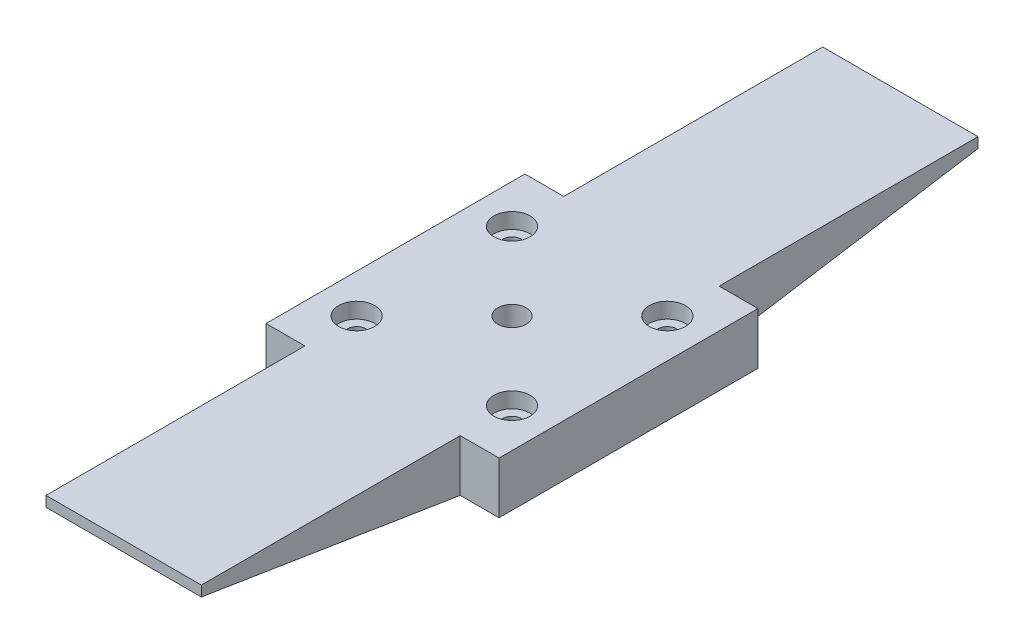
SolidWorks part; units mm, degrees
ref_plane "Front Plane" through (0, 0, 0) normal (0, 0, 1) x (1, 0, 0)
ref_plane "Top Plane" through (0, 0, 0) normal (0, 1, 0) x (1, 0, 0)
ref_plane "Right Plane" through (0, 0, 0) normal (1, 0, 0) x (0, 0, -1)
sketch "Sketch2" plane through (0, 0, 0) normal (1, 0, 0) x (0, 0, -1)
  line L0 (-75, 0) -> (75, 0)
  line L1 (75, 0) -> (75, -2)
  line L2 (75, -2) -> (25, -10)
  line L3 (25, -10) -> (-25, -10)
  line L5 (0, -33.3296) -> (0, 16.4312) construction
  line L6 (-75, -2) -> (-25, -10)
  line L7 (-75, 0) -> (-75, -2)
  point P9 (0, -10)
  point P11 (0, 0)
  dimension "D1" = 2
  dimension "D2" = 75
  dimension "D3" = 25
  dimension "D4" = 10
extrude "Boss-Extrude1" add sketch "Sketch2" along normal blind 45
sketch "Sketch3" plane through (0, -10, 0) normal (0, -1, 0) x (1, 0, 0)
  line L0 (22.5, -25) -> (22.5, 25) construction
  line L1 (45, -25) -> (0, -25) construction
  line L2 (45, 25) -> (0, 25) construction
  line L3 (0, 0) -> (45, 0) construction
  line L4 (45, 25) -> (45, -25) construction
  circle A0 centre (7.5, 15) radius 3.5
  circle A1 centre (37.5, 15) radius 3.5
  circle A2 centre (37.5, -15) radius 3.5
  circle A3 centre (7.5, -15) radius 3.5
  point P19 (0, 0)
  point P20 (0, 0)
  point P21 (0, 0)
  point P22 (0, 0)
  point P25 (60.2842, 17.7346)
  dimension "D1" = 7
  dimension "D2" = 7
  dimension "D3" = 7
  dimension "D4" = 7
  dimension "D5" = 15
  dimension "D6" = 15
  dimension "D7" = 15
  dimension "D8" = 15
extrude "Cut-Extrude1" cut sketch "Sketch3" against normal blind 2
sketch "Sketch4" plane through (0, -8, 0) normal (0, -1, 0) x (1, 0, 0)
  circle A0 centre (7.5, 15) radius 1.75
  circle A1 centre (7.5, -15) radius 1.75
  circle A2 centre (37.5, -15) radius 1.75
  circle A3 centre (37.5, 15) radius 1.75
  dimension "D1" = 3.5
  dimension "D2" = 3.5
  dimension "D3" = 3.5
  dimension "D4" = 3.5
extrude "Cut-Extrude2" cut sketch "Sketch4" against normal up to surface (8 mm away) up to face at (22.5, 0, 0)
sketch "Sketch5" plane through (0, 0, 0) normal (0, 1, 0) x (1, 0, 0)
  circle A0 centre (7.5, 15) radius 3.5
  circle A1 centre (37.5, 15) radius 3.5
  circle A2 centre (7.5, -15) radius 3.5
  circle A3 centre (37.5, -15) radius 3.5
  dimension "D1" = 7
  dimension "D2" = 7
  dimension "D3" = 7
  dimension "D4" = 7
extrude "Cut-Extrude3" cut sketch "Sketch5" against normal blind 3
sketch "Sketch6" plane through (45, 0, 0) normal (1, 0, 0) x (0, 0, -1)
  line L0 (25, -10) -> (25, 0)
  line L1 (75, 0) -> (-75, 0) construction
  line L2 (-25, -10) -> (-25, 0)
  line L3 (25, -10) -> (75, -2) construction
  line L4 (-75, -2) -> (-25, -10) construction
  line L6 (25, -10) -> (75, -2)
  line L7 (-75, -2) -> (-25, -10)
  line L8 (-75, 0) -> (-75, -2) construction
  line L9 (75, 0) -> (25, 0)
  line L10 (-25, 0) -> (-75, 0)
  line L11 (75, -2) -> (75, 0) construction
  line L12 (-75, 0) -> (-75, -2)
  line L13 (75, -2) -> (75, 0)
extrude "Cut-Extrude4" cut sketch "Sketch6" against normal blind 7.5
ref_plane "Plane1" through (22.5, 0, 0) normal (1, 0, 0) x (0, 0, -1)
mirror "Mirror1" about plane through (22.5, 0, 0) normal (1, 0, 0) of "Cut-Extrude4"
sketch "Sketch8" plane through (0, -10, 0) normal (0, -1, 0) x (1, 0, 0)
  line L0 (0, 0) -> (45, 0) construction
  line L1 (45, 25) -> (45, -25) construction
  circle A0 centre (22.5, 0) radius 2.75
  dimension "D1" = 5.5
extrude "Cut-Extrude5" cut sketch "Sketch8" against normal up to surface (10 mm away) up to face at (37.5, 0, -11.5)
